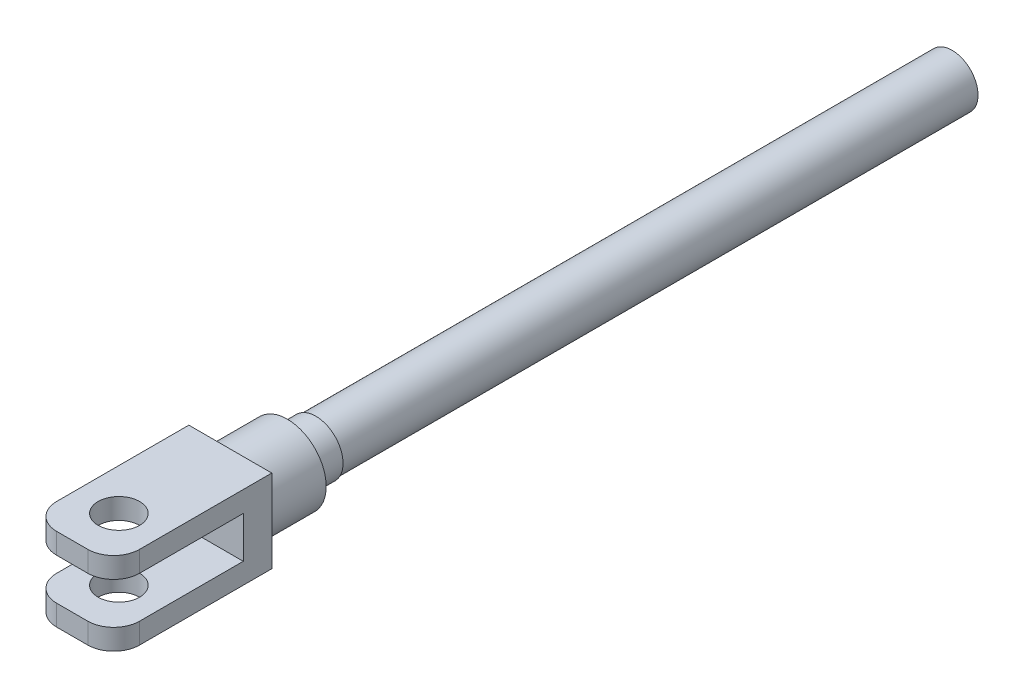
SolidWorks part; units mm, degrees
ref_plane "Front Plane" through (0, 0, 0) normal (0, 0, 1) x (1, 0, 0)
ref_plane "Top Plane" through (0, 0, 0) normal (0, 1, 0) x (1, 0, 0)
ref_plane "Right Plane" through (0, 0, 0) normal (1, 0, 0) x (0, 0, -1)
sketch "Sketch1" plane through (0, 0, 0) normal (0, 0, 1) x (1, 0, 0)
  circle A0 centre (0, 0) radius 10
  dimension "D1" = 20
extrude "Boss-Extrude1" add sketch "Sketch1" along normal blind 245.53
sketch "Sketch2" plane through (0, 0, 245.53) normal (0, 0, 1) x (1, 0, 0)
  circle A0 centre (0, 0) radius 10.5
  dimension "D1" = 21
extrude "Boss-Extrude2" add sketch "Sketch2" along normal blind 11
sketch "Sketch3" plane through (0, 0, 256.53) normal (0, 0, 1) x (1, 0, 0)
  circle A0 centre (0, 0) radius 15
  dimension "D1" = 30
extrude "Boss-Extrude3" add sketch "Sketch3" along normal blind 22
sketch "Sketch4" plane through (0, 0, 278.53) normal (0, 0, 1) x (1, 0, 0)
  line L1 (-16, -16) -> (16, -16)
  line L2 (-16, -16) -> (-16, 16)
  line L3 (-16, 16) -> (16, 16)
  line L4 (16, -16) -> (16, 16)
  line L5 (-16, -16) -> (16, 16) construction
  line L6 (-16, 16) -> (16, -16) construction
  point P0 (0, 0)
  dimension "D1" = 32
  dimension "D2" = 32
extrude "Boss-Extrude4" add sketch "Sketch4" along normal blind 61
sketch "Sketch5" plane through (-16, 0, 0) normal (-1, 0, 0) x (0, 0, 1)
  line L0 (289.53, -8) -> (339.53, -8)
  line L1 (278.53, 16) -> (342.53, 16) construction
  line L2 (278.53, 16) -> (278.53, -16) construction
  line L3 (278.53, -16) -> (339.53, -16) construction
  line L4 (339.53, 8) -> (339.53, -8)
  line L5 (289.53, 8) -> (289.53, -8)
  line L6 (289.53, 8) -> (339.53, 8)
  line L7 (278.53, 0) -> (339.53, 0) construction
  line L8 (339.53, 16) -> (339.53, -16) construction
  point P14 (339.53, 0)
  dimension "D1" = 16
  dimension "D2" = 11
extrude "Cut-Extrude1" cut sketch "Sketch5" against normal blind 58
sketch "Sketch6" plane through (0, 16, 0) normal (0, 1, 0) x (1, 0, 0)
  line L0 (0, -278.53) -> (0, -321.53) construction
  line L1 (-16, -278.53) -> (16, -278.53) construction
  line L2 (-16, -278.53) -> (-16, -329.53) construction
  line L3 (-6, -339.53) -> (6, -339.53) construction
  line L4 (16, -278.53) -> (16, -329.53) construction
  circle A0 centre (0, -321.53) radius 8
  arc A1 (-16, -329.53) -> (-6, -339.53) centre (-6, -329.53) ccw construction
  arc A2 (6, -339.53) -> (16, -329.53) centre (6, -329.53) ccw construction
  point P14 (16, -339.53)
  dimension "D1" = 16
  dimension "D3" = 10
  dimension "D2" = 43
extrude "Cut-Extrude2" cut sketch "Sketch6" against normal blind 58
fillet "Fillet1" radius 10 4 edges at (16, -12, 339.53) (16, 12, 339.53) (-16, -12, 339.53) (-16, 12, 339.53)
